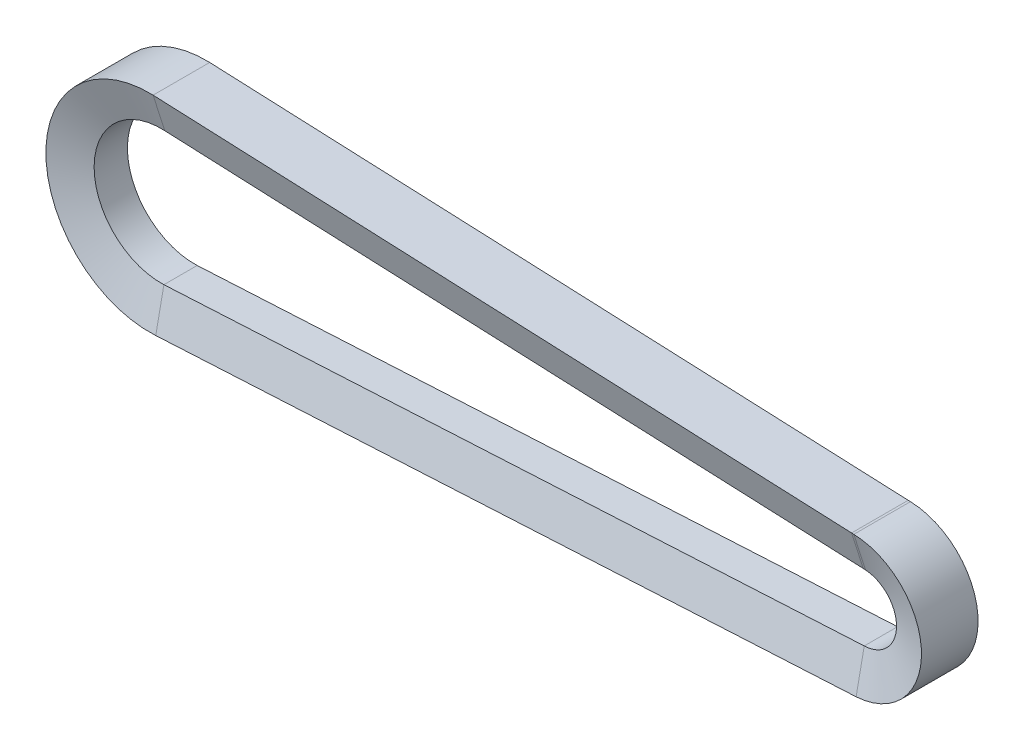
SolidWorks part; units mm, degrees
ref_plane "Front Plane" through (0, 0, 0) normal (0, 0, 1) x (1, 0, 0)
ref_plane "Top Plane" through (0, 0, 0) normal (0, 1, 0) x (1, 0, 0)
ref_plane "Right Plane" through (0, 0, 0) normal (1, 0, 0) x (0, 0, -1)
sketch "Sketch1" plane through (0, 0, 0) normal (0, 0, 1) x (1, 0, 0)
  line L0 (0, 0) -> (5.4931, 0) construction
  line L1 (0, 0) -> (0, 3.4501) construction
  line L2 (0.6629, 15.4858) -> (-209.8017, 24.4949)
  line L3 (-209.5331, -26.6953) -> (0.8254, -15.478)
  arc A0 (0.8254, -15.478) -> (0.6629, 15.4858) centre (0, 0) ccw
  arc A1 (-209.8017, 24.4949) -> (-209.5331, -26.6953) centre (-210.8976, -1.1067) ccw
  point P3 (-213.5337, 0.949)
  point P9 (0, 0)
  point P10 (0, 0)
  point P11 (0.0784, 0.051)
  point P12 (-17.0771, 14.1297)
  point P13 (0, 0)
  point P15 (0, 3.4501)
  point P16 (5.4931, 0)
  point P17 (2.573, 15.2849)
  dimension "D1" = 25.625
  dimension "D2" = 15.5
  dimension "D3" = 210.9005
sketch "Sketch2" plane through (0, 0, 0) normal (1, 0, 0) x (0, 0, -1)
  line L0 (8.5, 21) -> (-8.5, 21)
  line L1 (-8.5, 21) -> (-5, 10)
  line L2 (-5, 10) -> (5, 10)
  line L3 (5, 10) -> (8.5, 21)
  point P5 (-6.5368, 4.4858)
  dimension "D1" = 11
  dimension "D2" = 17
  dimension "D3" = 10
  dimension "D4" = 21
sweep "Sweep1" add profiles "Sketch2" path "Sketch1"
